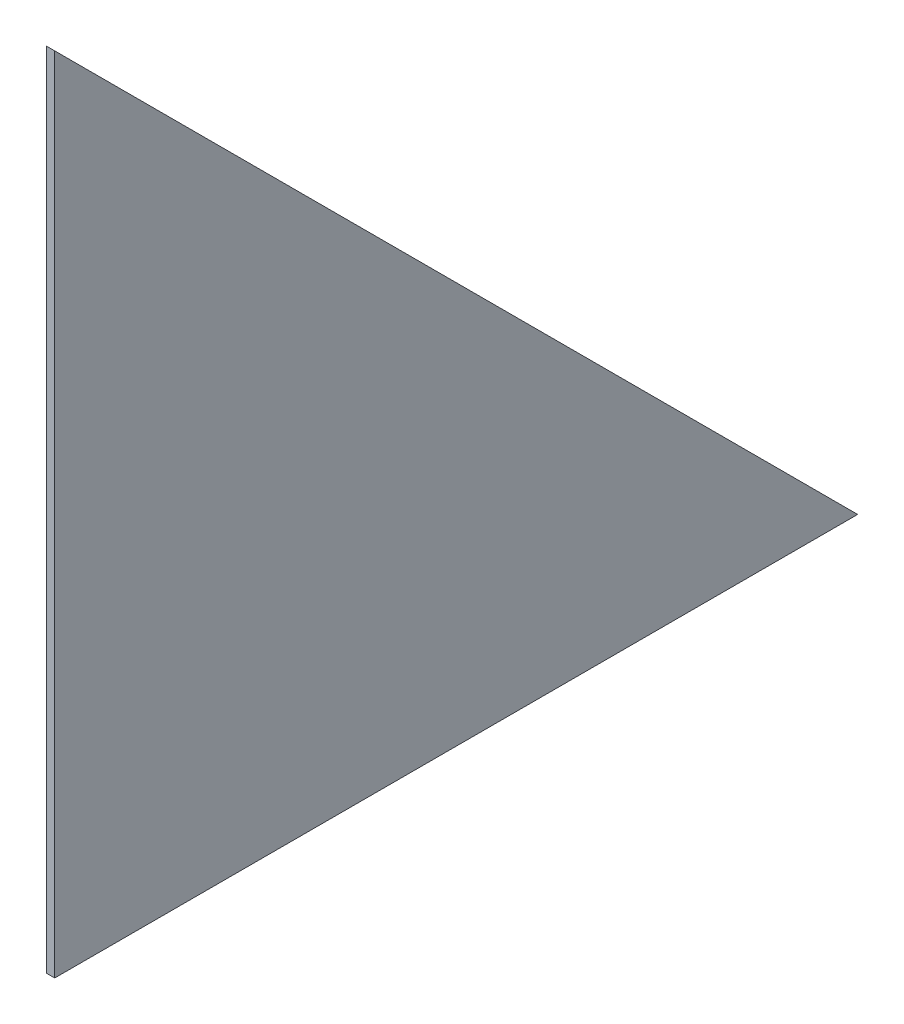
SolidWorks part; units mm, degrees
ref_plane "Plan de face" through (0, 0, 0) normal (0, 0, 1) x (1, 0, 0)
ref_plane "Plan de dessus" through (0, 0, 0) normal (0, 1, 0) x (1, 0, 0)
ref_plane "Plan de droite" through (0, 0, 0) normal (1, 0, 0) x (0, 0, -1)
sketch "Esquisse1" plane through (0, 0, 0) normal (1, 0, 0) x (0, 0, -1)
  line L0 (0, 0) -> (0, 382)
  line L1 (0, 382) -> (382, 0)
  line L2 (382, 0) -> (0, 0)
  dimension "D1" = 382
extrude "Boss.-Extru.1" add sketch "Esquisse1" along normal blind 4
